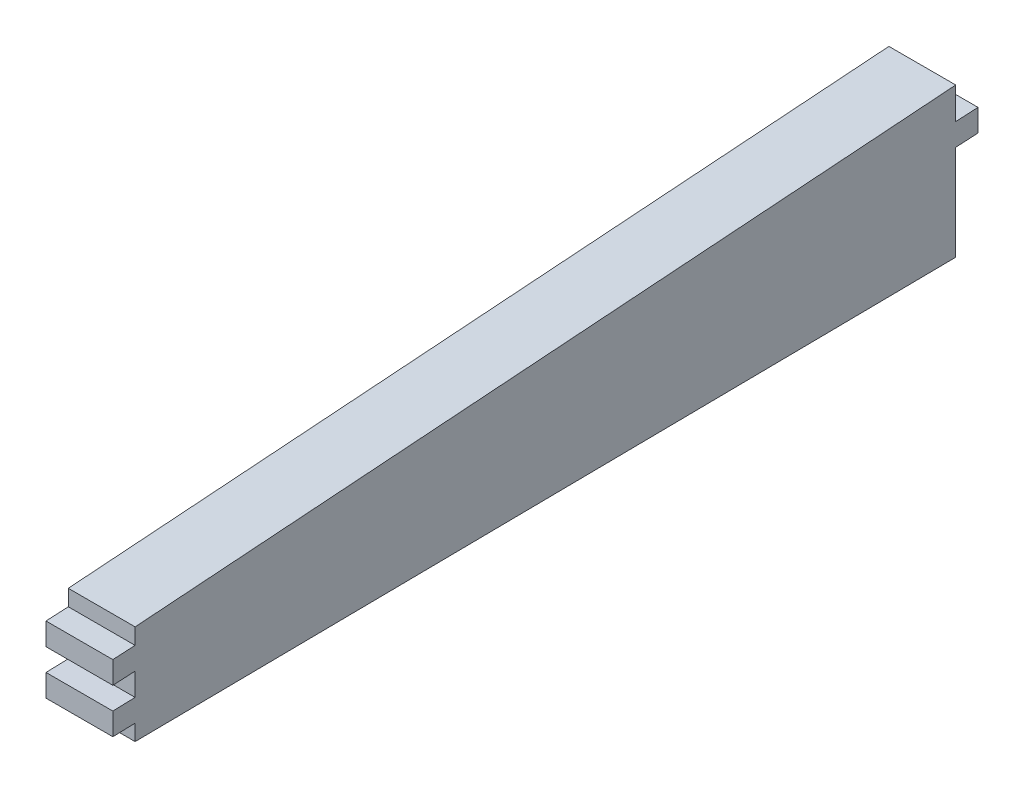
SolidWorks part; units mm, degrees
material "Balsa"
ref_plane "Front Plane" through (0, 0, 0) normal (0, 0, 1) x (1, 0, 0)
ref_plane "Top Plane" through (0, 0, 0) normal (0, 1, 0) x (1, 0, 0)
ref_plane "Right Plane" through (0, 0, 0) normal (1, 0, 0) x (0, 0, -1)
ref_plane "Plane4" through (243.0177, 362.3687, 1500.7812) normal (0, -1, 0) x (-1, 0, 0)
sketch "Sketch2" plane through (243.0177, 0, 0) normal (1, 0, 0) x (0, 0, -1)
  line L1 (-1497.6062, 359.2899) -> (-1500.7812, 359.1937) construction
  line L2 (-1500.7812, 359.1937) -> (-1500.7812, 356.0187) construction
  line L3 (-1500.7812, 356.0187) -> (-1497.6062, 356.1149) construction
  line L5 (-1497.6062, 365.7113) -> (-1500.7812, 365.5437) construction
  line L6 (-1500.7812, 365.5437) -> (-1500.7812, 362.3687) construction
  line L7 (-1500.7812, 362.3687) -> (-1497.6062, 362.5363) construction
  line L9 (-1380.6604, 368.7092) -> (-1377.4854, 368.8768) construction
  line L10 (-1377.4854, 368.8768) -> (-1377.4854, 372.0518) construction
  line L11 (-1377.4854, 372.0518) -> (-1380.6604, 371.8842) construction
  line L12 (-1497.6062, 353.8317) -> (-1500.7812, 353.7962) construction
  line L13 (-1497.6062, 367.9944) -> (-1500.7812, 367.7662) construction
  line L14 (-1377.4854, 355.1762) -> (-1380.6604, 355.1406) construction
  line L15 (-1377.4854, 376.6305) -> (-1380.6604, 376.4022) construction
  line L17 (-1497.6062, 359.2899) -> (-1500.7812, 359.1937)
  line L18 (-1500.7812, 359.1937) -> (-1500.7812, 356.0187)
  line L19 (-1500.7812, 356.0187) -> (-1497.6062, 356.1149)
  line L21 (-1497.6062, 365.7113) -> (-1500.7812, 365.5437)
  line L22 (-1500.7812, 365.5437) -> (-1500.7812, 362.3687)
  line L23 (-1500.7812, 362.3687) -> (-1497.6062, 362.5363)
  line L25 (-1380.6604, 368.7092) -> (-1377.4854, 368.8768)
  line L26 (-1377.4854, 368.8768) -> (-1377.4854, 372.0518)
  line L27 (-1377.4854, 372.0518) -> (-1380.6604, 371.8842)
  line L28 (-1497.6062, 353.8317) -> (-1500.7812, 353.7962) construction
  line L29 (-1497.6062, 367.9944) -> (-1500.7812, 367.7662) construction
  line L30 (-1377.4854, 355.1762) -> (-1380.6604, 355.1406) construction
  line L31 (-1377.4854, 376.6305) -> (-1380.6604, 376.4022) construction
  line L32 (-1380.6604, 376.4022) -> (-1380.6604, 371.8842)
  line L33 (-1380.6604, 355.1406) -> (-1380.6604, 368.7092)
  line L34 (-1380.6604, 355.1406) -> (-1497.6062, 353.8317)
  line L35 (-1497.6062, 353.8317) -> (-1497.6062, 356.1149)
  line L36 (-1497.6062, 359.2899) -> (-1497.6062, 362.5363)
  line L37 (-1497.6062, 365.7113) -> (-1497.6062, 367.9944)
  line L38 (-1497.6062, 367.9944) -> (-1380.6604, 376.4022)
extrude "Boss-Extrude1" add sketch "Sketch2" along normal up to surface (9.525 mm away)
